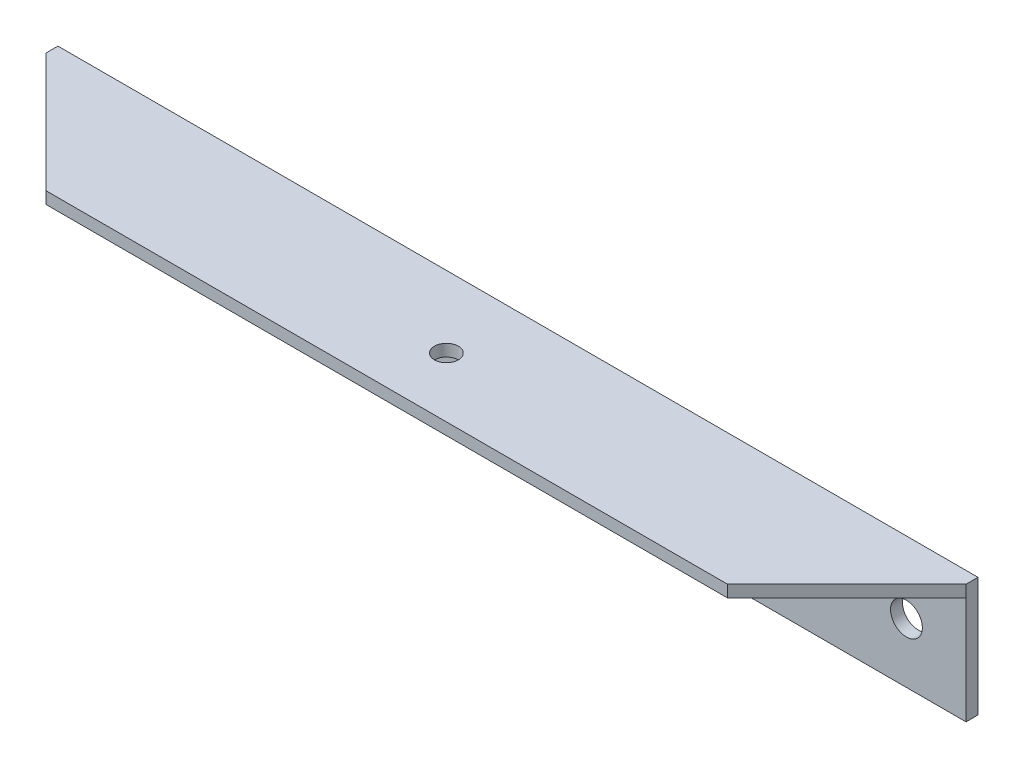
SolidWorks part; units mm, degrees
ref_plane "Front Plane" through (0, 0, 0) normal (0, 0, 1) x (1, 0, 0)
ref_plane "Top Plane" through (0, 0, 0) normal (0, 1, 0) x (1, 0, 0)
ref_plane "Right Plane" through (0, 0, 0) normal (1, 0, 0) x (0, 0, -1)
sketch "Sketch1" plane through (0, 0, 0) normal (0, 0, 1) x (1, 0, 0)
  line L0 (-115.7, 0) -> (115.7, 0)
  line L1 (115.7, 0) -> (115.7, -30)
  line L2 (115.7, -30) -> (-115.7, -30)
  line L3 (-115.7, -30) -> (-115.7, 0)
  point P4 (0, 0)
  dimension "D1" = 231.4
  dimension "D2" = 30
extrude "Boss-Extrude1" add sketch "Sketch1" along normal blind 3
sketch "Sketch2" plane through (0, 0, 0) normal (0, 1, 0) x (1, 0, 0)
  line L0 (115.7, -3) -> (-115.7, -3) construction
  line L1 (-115.7, -3) -> (115.7, -3)
  line L2 (-85.7, -33) -> (85.7, -33)
  line L3 (-115.7, -3) -> (-85.7, -33)
  line L4 (115.7, -3) -> (85.7, -33)
  dimension "D1" = 45
  dimension "D2" = 45
  dimension "D3" = 30
extrude "Boss-Extrude2" add sketch "Sketch2" against normal blind 3
sketch "Sketch3" plane through (0, 0, 0) normal (0, 0, -1) x (-1, 0, 0)
  line L0 (-115.7, -30) -> (-100.7, -30) construction
  line L1 (115.7, -30) -> (-115.7, -30) construction
  line L3 (-100.7, -30) -> (-100.7, -15) construction
  line L4 (115.7, -30) -> (100.7, -30) construction
  line L5 (100.7, -30) -> (100.7, -15) construction
  dimension "D1" = 15
  dimension "D2" = 15
  dimension "D3" = 15
  dimension "D4" = 15
hole_wizard "Ø8.0 (8) Diameter Hole1" positions "Sketch4" profile "Sketch5" hole size "Ø8.0" standard "AS" end condition through all
sketch "Sketch4" plane through (0, 0, 0) normal (0, 0, -1) x (-1, 0, 0)
  point P0 (-100.7, -15)
  point P3 (100.7, -15)
sketch "Sketch5" plane through (100.7, -15, 0) normal (1, 0, 0) x (0, 1, 0)
  line L0 (0, 0) -> (0, 33)
  line L1 (0, 33) -> (4, 33)
  line L2 (4, 33) -> (4, 0)
  line L5 (4, 0) -> (0, 0)
  line L11 (0, -6.35) -> (0, 107.95) construction
  dimension "Thru Hole Dia." = 8
  dimension "Thru Hole Depth" = 33
sketch "Sketch6" plane through (0, 0, 0) normal (0, 0, -1) x (-1, 0, 0)
  line L0 (115.7, -30) -> (62.5, -30) construction
  line L1 (115.7, -30) -> (-115.7, -30) construction
  line L2 (62.5, -30) -> (62.5, -15) construction
  dimension "D1" = 53.2
  dimension "D2" = 15
hole_wizard "Ø10.0 (10) Diameter Hole1" positions "Sketch7" profile "Sketch8" hole size "Ø10.0" standard "AS" end condition through all
sketch "Sketch7" plane through (0, 0, 0) normal (0, 0, -1) x (-1, 0, 0)
  point P0 (62.5, -15)
sketch "Sketch8" plane through (-62.5, -15, 0) normal (1, 0, 0) x (0, 1, 0)
  line L0 (0, 0) -> (0, 33)
  line L1 (0, 33) -> (5, 33)
  line L2 (5, 33) -> (5, 0)
  line L5 (5, 0) -> (0, 0)
  line L11 (0, -6.35) -> (0, 107.95) construction
  dimension "Thru Hole Dia." = 10
  dimension "Thru Hole Depth" = 33
sketch "Sketch9" plane through (0, 0, 0) normal (0, 1, 0) x (1, 0, 0)
  line L0 (-85.7, -33) -> (85.7, -33) construction
  line L1 (-85.7, -33) -> (85.7, -33) construction
  line L2 (0, -33) -> (0, -18) construction
  dimension "D1" = 15
hole_wizard "Ø6.0 (6) Diameter Hole1" positions "Sketch10" profile "Sketch11" hole size "Ø6.0" standard "AS" end condition through all
sketch "Sketch10" plane through (0, 0, 0) normal (0, 1, 0) x (1, 0, 0)
  point P0 (0, -18)
sketch "Sketch11" plane through (0, 0, 18) normal (1, 0, 0) x (0, 0, 1)
  line L0 (0, 0) -> (0, 30)
  line L1 (0, 30) -> (3, 30)
  line L2 (3, 30) -> (3, 0)
  line L5 (3, 0) -> (0, 0)
  line L11 (0, -6.35) -> (0, 107.95) construction
  dimension "Thru Hole Dia." = 6
  dimension "Thru Hole Depth" = 30
